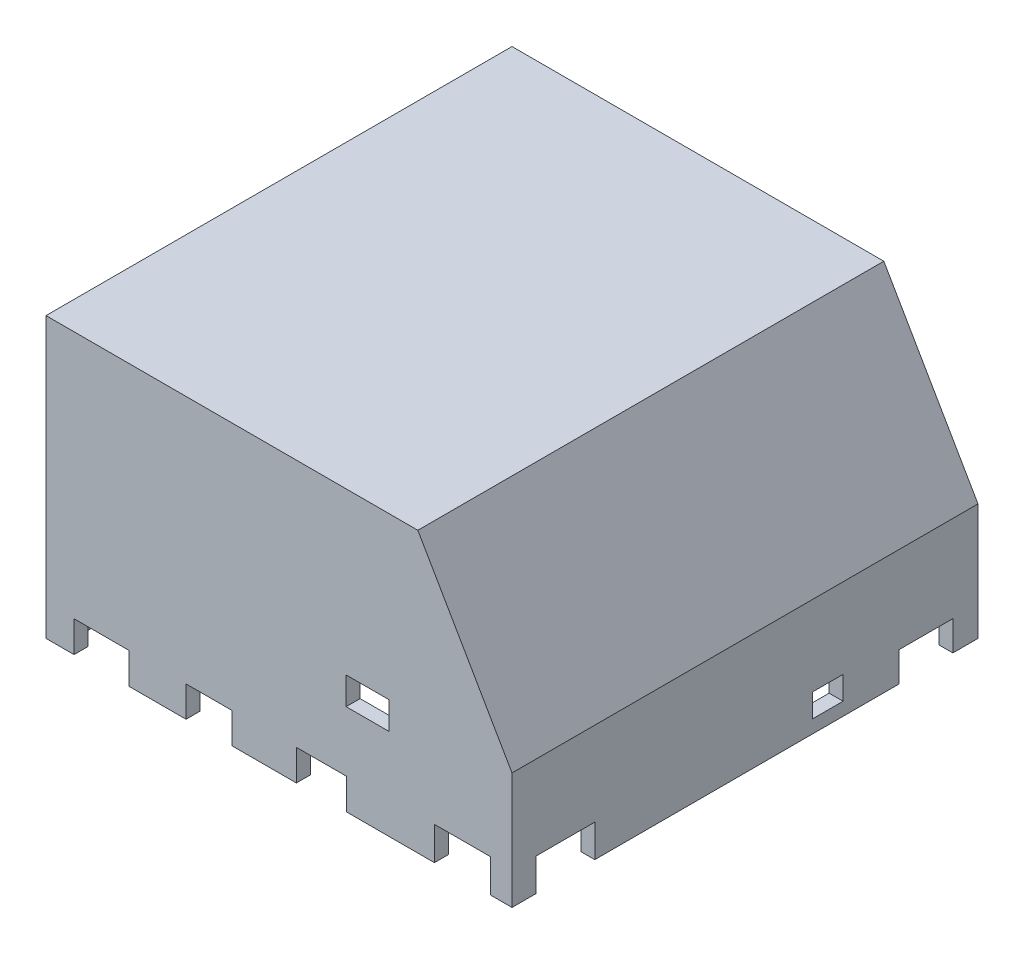
SolidWorks part; units mm, degrees
ref_plane "Front Plane" through (0, 0, 0) normal (0, 0, 1) x (1, 0, 0)
ref_plane "Top Plane" through (0, 0, 0) normal (0, 1, 0) x (1, 0, 0)
ref_plane "Right Plane" through (0, 0, 0) normal (1, 0, 0) x (0, 0, -1)
sketch "Sketch1" plane through (0, 0, 0) normal (0, 0, 1) x (1, 0, 0)
  line L0 (-50, 12.5) -> (-50, 47.5)
  line L1 (-50, -12.5) -> (50, -12.5)
  line L2 (-50, -12.5) -> (-50, 12.5)
  line L3 (-50, 12.5) -> (50, 12.5) construction
  line L4 (50, -12.5) -> (50, 12.5)
  line L5 (-50, -12.5) -> (50, 12.5) construction
  line L6 (-50, 12.5) -> (50, -12.5) construction
  line L7 (-50, 47.5) -> (29.7927, 47.5)
  line L8 (29.7927, 47.5) -> (50, 12.5)
  point P0 (0, 0)
  dimension "D1" = 100
  dimension "D2" = 25
  dimension "D3" = 60
  dimension "D4" = 60
extrude "Boss-Extrude1" add sketch "Sketch1" along normal blind 100 contours L8 L4 L1 L2 L0 L7
shell "Shell1" thickness 3
sketch "Sketch2" plane through (-50, 0, 0) normal (-1, 0, 0) x (0, 0, 1)
  line L0 (100, -12.5) -> (0, -12.5) construction
  line L1 (23.8769, -12.5) -> (79.8925, -12.5)
  line L2 (23.8769, -12.5) -> (23.8769, 22.5)
  line L3 (23.8769, 22.5) -> (79.8925, 22.5)
  line L4 (79.8925, -12.5) -> (79.8925, 22.5)
  line L5 (23.8769, -12.5) -> (79.8925, 22.5) construction
  line L6 (23.8769, 22.5) -> (79.8925, -12.5) construction
  point P4 (51.8847, 5)
  dimension "D1" = 35
extrude "Cut-Extrude1" cut sketch "Sketch2" against normal blind 10
sketch "Sketch3" plane through (50, 0, 0) normal (1, 0, 0) x (0, 0, -1)
  line L0 (-50.3131, -12.5) -> (-50.3131, 6.4865) construction
  line L1 (-100, -12.5) -> (0, -12.5) construction
  line L3 (-94.8455, -12.5) -> (-82.2389, -12.5)
  line L4 (-94.8455, -12.5) -> (-94.8455, -5.5198)
  line L5 (-94.8455, -5.5198) -> (-82.2389, -5.5198)
  line L6 (-82.2389, -12.5) -> (-82.2389, -5.5198)
  line L7 (-94.8455, -12.5) -> (-82.2389, -5.5198) construction
  line L8 (-94.8455, -5.5198) -> (-82.2389, -12.5) construction
  line L9 (-5.3987, -12.5) -> (-16.9138, -12.5)
  line L10 (-5.3987, -12.5) -> (-5.3987, -6.1201)
  line L11 (-5.3987, -6.1201) -> (-16.9138, -6.1201)
  line L12 (-16.9138, -12.5) -> (-16.9138, -6.1201)
  line L13 (-5.3987, -12.5) -> (-16.9138, -6.1201) construction
  line L14 (-5.3987, -6.1201) -> (-16.9138, -12.5) construction
  point P8 (-88.5422, -9.0099)
  point P13 (-11.1563, -9.3101)
extrude "Cut-Extrude2" cut sketch "Sketch3" against normal blind 10
sketch "Sketch4" plane through (0, 0, 100) normal (0, 0, 1) x (1, 0, 0)
  line L1 (14.4088, 12.9154) -> (23.578, 12.9154)
  line L2 (14.4088, 12.9154) -> (14.4088, 7.0209)
  line L3 (14.4088, 7.0209) -> (23.578, 7.0209)
  line L4 (23.578, 12.9154) -> (23.578, 7.0209)
  line L5 (14.4088, 12.9154) -> (23.578, 7.0209) construction
  line L6 (14.4088, 7.0209) -> (23.578, 12.9154) construction
  point P4 (18.9934, 9.9681)
extrude "Cut-Extrude3" cut sketch "Sketch4" against normal blind 10
sketch "Sketch5" plane through (-50, 0, 0) normal (-1, 0, 0) x (0, 0, 1)
  line L0 (50, 47.5) -> (50, 18.7219) construction
  line L1 (5.2219, -4.6054) -> (11.9979, -4.6054)
  line L2 (5.2219, -4.6054) -> (5.2219, -9.6596)
  line L3 (5.2219, -9.6596) -> (11.9979, -9.6596)
  line L4 (11.9979, -4.6054) -> (11.9979, -9.6596)
  line L5 (5.2219, -4.6054) -> (11.9979, -9.6596) construction
  line L6 (5.2219, -9.6596) -> (11.9979, -4.6054) construction
  line L11 (100, 47.5) -> (0, 47.5) construction
  line L12 (94.7781, -9.6596) -> (88.0021, -9.6596)
  line L13 (88.0021, -4.6054) -> (88.0021, -9.6596)
  line L14 (94.7781, -4.6054) -> (88.0021, -4.6054)
  line L15 (94.7781, -4.6054) -> (94.7781, -9.6596)
  point P4 (8.6099, -7.1325)
extrude "Cut-Extrude4" cut sketch "Sketch5" against normal blind 10
sketch "Sketch6" plane through (0, 0, 100) normal (0, 0, 1) x (1, 0, 0)
  line L0 (-50, -12.5) -> (50, -12.5) construction
  line L1 (45.3423, -12.5) -> (33.3518, -12.5)
  line L2 (45.3423, -12.5) -> (45.3423, -5.3727)
  line L3 (45.3423, -5.3727) -> (33.3518, -5.3727)
  line L4 (33.3518, -12.5) -> (33.3518, -5.3727)
  line L5 (45.3423, -12.5) -> (33.3518, -5.3727) construction
  line L6 (45.3423, -5.3727) -> (33.3518, -12.5) construction
  point P4 (39.3471, -8.9363)
extrude "Cut-Extrude5" cut sketch "Sketch6" against normal through all
sketch "Sketch8" plane through (50, 0, 0) normal (1, 0, 0) x (0, 0, -1)
  line L1 (-35.5126, -9.6977) -> (-28.9496, -9.6977)
  line L2 (-35.5126, -9.6977) -> (-35.5126, -4.692)
  line L3 (-35.5126, -4.692) -> (-28.9496, -4.692)
  line L4 (-28.9496, -9.6977) -> (-28.9496, -4.692)
  line L5 (-35.5126, -9.6977) -> (-28.9496, -4.692) construction
  line L6 (-35.5126, -4.692) -> (-28.9496, -9.6977) construction
  point P4 (-32.2311, -7.1948)
extrude "Cut-Extrude6" cut sketch "Sketch8" against normal blind 10
sketch "Sketch9" plane through (0, 0, 100) normal (0, 0, 1) x (1, 0, 0)
  line L0 (-50, -12.5) -> (33.3518, -12.5) construction
  line L1 (-43.9821, -12.5) -> (-32.1931, -12.5)
  line L2 (-43.9821, -12.5) -> (-43.9821, -5.8261)
  line L3 (-43.9821, -5.8261) -> (-32.1931, -5.8261)
  line L4 (-32.1931, -12.5) -> (-32.1931, -5.8261)
  line L5 (-43.9821, -12.5) -> (-32.1931, -5.8261) construction
  line L6 (-43.9821, -5.8261) -> (-32.1931, -12.5) construction
  line L8 (3.7281, -12.5) -> (14.4592, -12.5)
  line L9 (3.7281, -12.5) -> (3.7281, -5.8765)
  line L10 (3.7281, -5.8765) -> (14.4592, -5.8765)
  line L11 (14.4592, -12.5) -> (14.4592, -5.8765)
  line L12 (3.7281, -12.5) -> (14.4592, -5.8765) construction
  line L13 (3.7281, -5.8765) -> (14.4592, -12.5) construction
  line L18 (-19.9506, -12.5) -> (-10.1265, -12.5)
  line L19 (-19.9506, -12.5) -> (-19.9506, -5.9269)
  line L20 (-19.9506, -5.9269) -> (-10.1265, -5.9269)
  line L21 (-10.1265, -12.5) -> (-10.1265, -5.9269)
  line L22 (-19.9506, -12.5) -> (-10.1265, -5.9269) construction
  line L23 (-19.9506, -5.9269) -> (-10.1265, -12.5) construction
  point P4 (-38.0876, -9.1631)
  point P11 (9.0937, -9.1882)
  point P12 (-32.1931, -5.8261)
  point P13 (0.5542, -5.7757)
  point P18 (-15.0385, -9.2134)
  point P19 (-19.9506, -5.9269)
  point P20 (3.7281, -5.8765)
extrude "Cut-Extrude7" cut sketch "Sketch9" against normal through all
